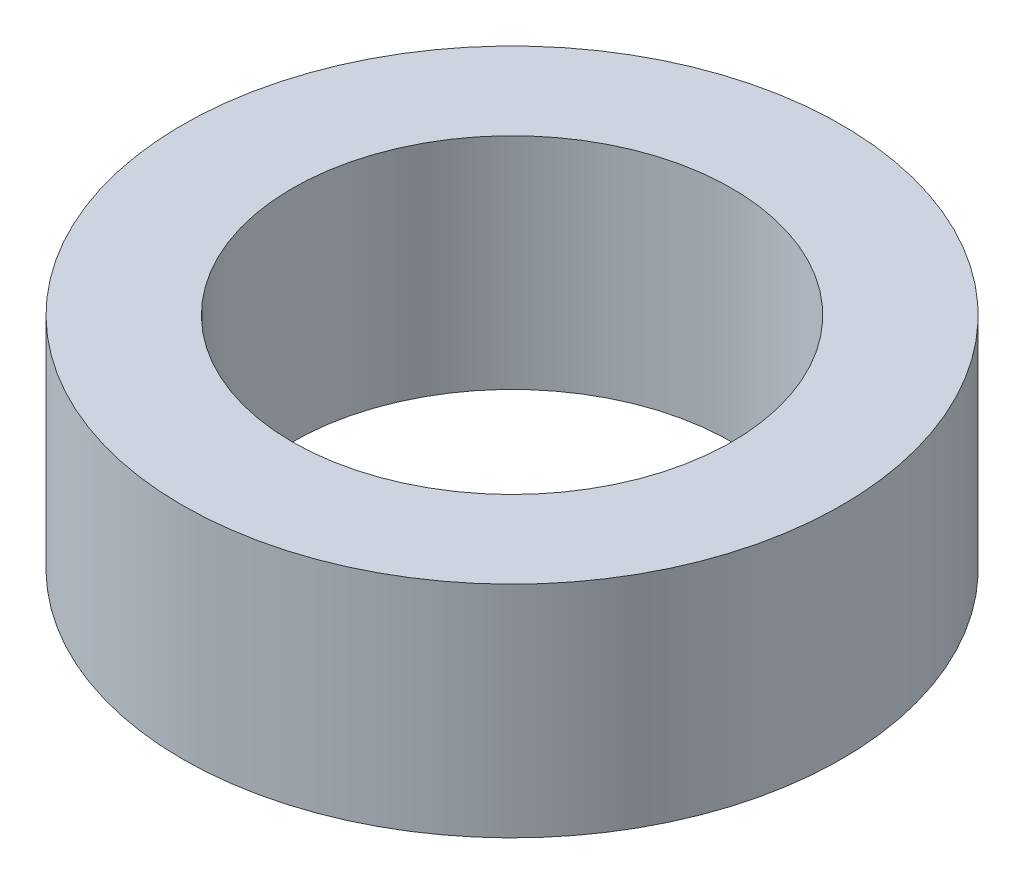
SolidWorks part; units mm, degrees
material "1023 Carbon Steel Sheet (SS)"
ref_plane "Front Plane" through (0, 0, 0) normal (0, 0, 1) x (1, 0, 0)
ref_plane "Top Plane" through (0, 0, 0) normal (0, 1, 0) x (1, 0, 0)
ref_plane "Right Plane" through (0, 0, 0) normal (1, 0, 0) x (0, 0, -1)
sketch "Sketch1" plane through (0, 0, 0) normal (0, 1, 0) x (1, 0, 0)
  circle A0 centre (0, 0) radius 19.05
  circle A1 centre (0, 0) radius 12.7
  dimension "D1" = 38.1
  dimension "D2" = 25.4
extrude "Boss-Extrude2" add sketch "Sketch1" along normal blind 12.7 contours A0 A1
sketch "Sketch2" plane through (0, 0, 0) normal (1, 0, 0) x (0, 0, -1)
  line L1 (0, 0) -> (0, 12.7)
  line L2 (19.05, 12.7) -> (-19.05, 12.7) construction
  line L6 (-19.05, 0) -> (19.05, 0) construction
  line L9 (-19.05, 0) -> (-12.7, 0) construction
  line L10 (-18.9859, 0) -> (-12.7641, 0)
  arc A2 (-18.9859, 0) -> (-12.7641, 0) centre (-15.875, -0.635) cw
  point P18 (-15.875, 0)
  point P19 (-15.875, 2.54)
  dimension "D1" = 3.175
  dimension "D2" = 2.54
revolve "Cut-Revolve1" cut sketch "Sketch2" angle 360 about L1
